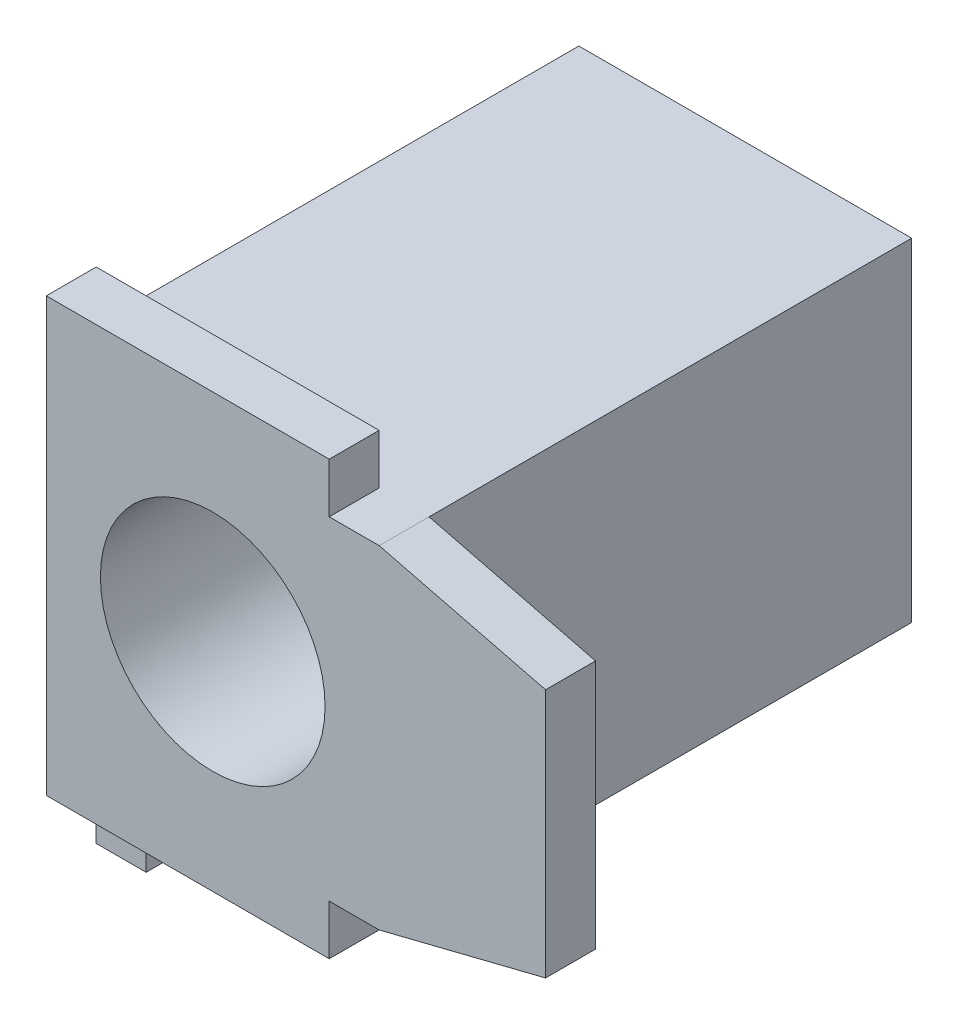
SolidWorks part; units mm, degrees
ref_plane "前视基准面" through (0, 0, 0) normal (0, 0, 1) x (1, 0, 0)
ref_plane "上视基准面" through (0, 0, 0) normal (0, 1, 0) x (1, 0, 0)
ref_plane "右视基准面" through (0, 0, 0) normal (1, 0, 0) x (0, 0, -1)
sketch "草图1" plane through (0, 0, 0) normal (0, 0, 1) x (1, 0, 0)
  line L1 (-10, 10) -> (10, 10)
  line L2 (-10, 10) -> (-10, -10)
  line L3 (-10, -10) -> (10, -10)
  line L4 (10, 10) -> (10, -10)
  line L5 (-10, 10) -> (10, -10) construction
  line L6 (-10, -10) -> (10, 10) construction
  circle A0 centre (0, 0) radius 6.75
  point P0 (0, 0)
  dimension "D3" = 13.5
  dimension "D1" = 20
  dimension "D2" = 20
extrude "凸台-拉伸1" add sketch "草图1" along normal blind 27
sketch "草图2" plane through (0, 0, 0) normal (0, 0, -1) x (-1, 0, 0)
  line L1 (-10, -10) -> (10, -10)
  line L2 (-10, -10) -> (-10, 10)
  line L3 (-10, 10) -> (10, 10)
  line L4 (10, -10) -> (10, 10)
  line L5 (-10, -10) -> (10, 10) construction
  line L6 (-10, 10) -> (10, -10) construction
  circle A0 centre (0, 0) radius 1.5
  point P0 (0, 0)
  dimension "D1" = 3
extrude "凸台-拉伸2" add sketch "草图2" along normal blind 5
sketch "草图3" plane through (10, 0, 0) normal (1, 0, 0) x (0, 0, -1)
  line L0 (-27, -10) -> (5, -10) construction
  line L1 (-27, 10) -> (-24, 10)
  line L2 (-27, 10) -> (-27, -10)
  line L3 (-27, -10) -> (-24, -10)
  line L4 (-24, 10) -> (-24, -10)
  dimension "D1" = 3
extrude "凸台-拉伸3" add sketch "草图3" along normal blind 10
sketch "草图4" plane through (0, 0, 24) normal (0, 0, -1) x (-1, 0, 0)
  line L0 (-20, 7.5) -> (-10, 10)
  line L1 (-20, -10) -> (-20, 10) construction
  line L2 (-20, 10) -> (-10, 10) construction
  line L3 (-20, 7.5) -> (-20, 10)
  line L4 (-20, 10) -> (-10, 10)
  dimension "D1" = 2.5
extrude "切除-拉伸1" cut sketch "草图4" against normal blind 10
mirror "镜向1" about plane through (0, 0, 0) normal (0, 1, 0) of "切除-拉伸1"
sketch "草图5" plane through (0, 10, 0) normal (0, 1, 0) x (1, 0, 0)
  line L1 (7, -24) -> (-10, -24)
  line L2 (7, -24) -> (7, -27)
  line L3 (7, -27) -> (-10, -27)
  line L4 (-10, -24) -> (-10, -27)
  dimension "D1" = 17
  dimension "D2" = 3
extrude "凸台-拉伸4" add sketch "草图5" along normal blind 3
mirror "镜向2" about plane through (0, 0, 0) normal (0, 1, 0) of "凸台-拉伸4"
sketch "草图7" plane through (-10, 0, 0) normal (-1, 0, 0) x (0, 0, 1)
  line L1 (-5, -10) -> (24, -10)
  line L2 (-5, -10) -> (-5, -17)
  line L3 (-5, -17) -> (24, -17)
  line L4 (24, -10) -> (24, -17)
  dimension "D1" = 29
  dimension "D2" = 7
extrude "凸台-拉伸5" add sketch "草图7" against normal blind 3
sketch "草图8" plane through (-10, 0, 0) normal (-1, 0, 0) x (0, 0, 1)
  circle A0 centre (19, -13) radius 2
  circle A1 centre (-1, -13) radius 2
extrude "切除-拉伸2" cut sketch "草图8" against normal blind 10
